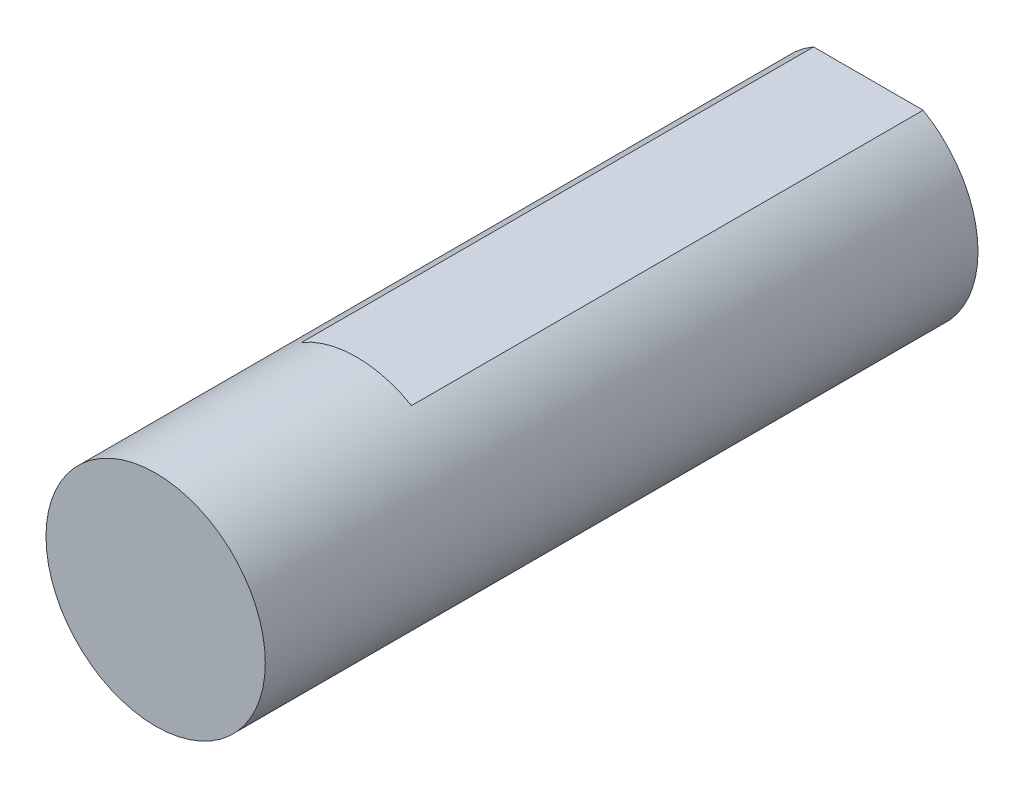
SolidWorks part; units mm, degrees
ref_plane "Front Plane" through (0, 0, 0) normal (0, 0, 1) x (1, 0, 0)
ref_plane "Top Plane" through (0, 0, 0) normal (0, 1, 0) x (1, 0, 0)
ref_plane "Right Plane" through (0, 0, 0) normal (1, 0, 0) x (0, 0, -1)
sketch "Sketch1" plane through (0, 0, 0) normal (0, 0, 1) x (1, 0, 0)
  line L0 (-3, 5.1962) -> (3, 5.1962)
  circle A0 centre (0, 0) radius 6
  dimension "D1" = 12
  dimension "D2" = 6
extrude "Boss-Extrude1" add sketch "Sketch1" along normal blind 39 contours A0
sketch "Sketch2" plane through (0, 0, 0) normal (0, 0, -1) x (-1, 0, 0)
  line L0 (-3, 5.1962) -> (3, 5.1962)
  circle A1 centre (0, 0) radius 6 construction
  circle A2 centre (0, 0) radius 6
  circle M3 centre (0, 0) radius 6
  dimension "D1" = 6
extrude "Cut-Extrude1" cut sketch "Sketch2" against normal blind 28 contours L0 M3
